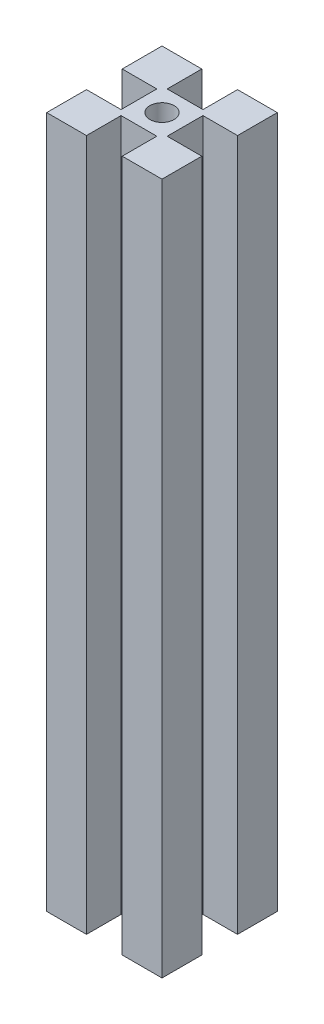
SolidWorks part; units mm, degrees
ref_plane "Front Plane" through (0, 0, 0) normal (0, 0, 1) x (1, 0, 0)
ref_plane "Top Plane" through (0, 0, 0) normal (0, 1, 0) x (1, 0, 0)
ref_plane "Right Plane" through (0, 0, 0) normal (1, 0, 0) x (0, 0, -1)
sketch "SK_P01_p2020" plane through (0, 0, 0) normal (0, 1, 0) x (1, 0, 0)
  line L0 (10, -10) -> (10, -3.1)
  line L1 (10, -3.1) -> (4, -3.1)
  line L2 (4, -3.1) -> (4, 3.1)
  line L3 (4, 3.1) -> (10, 3.1)
  line L4 (10, 3.1) -> (10, 10)
  line L5 (10, 10) -> (3.1, 10)
  line L6 (3.1, 10) -> (3.1, 4)
  line L7 (3.1, 4) -> (-3.1, 4)
  line L8 (-3.1, 4) -> (-3.1, 10)
  line L9 (-3.1, 10) -> (-10, 10)
  line L10 (-10, 10) -> (-10, 3.1)
  line L11 (-10, 3.1) -> (-4, 3.1)
  line L12 (-4, 3.1) -> (-4, -3.1)
  line L13 (-4, -3.1) -> (-10, -3.1)
  line L14 (-10, -3.1) -> (-10, -10)
  line L15 (-10, -10) -> (-3.1, -10)
  line L16 (-3.1, -10) -> (-3.1, -4)
  line L17 (-3.1, -4) -> (3.1, -4)
  line L18 (3.1, -4) -> (3.1, -10)
  line L19 (3.1, -10) -> (10, -10)
  circle A0 centre (0, 0) radius 2.1
extrude "P01_p2020" add sketch "SK_P01_p2020" along normal blind 120
